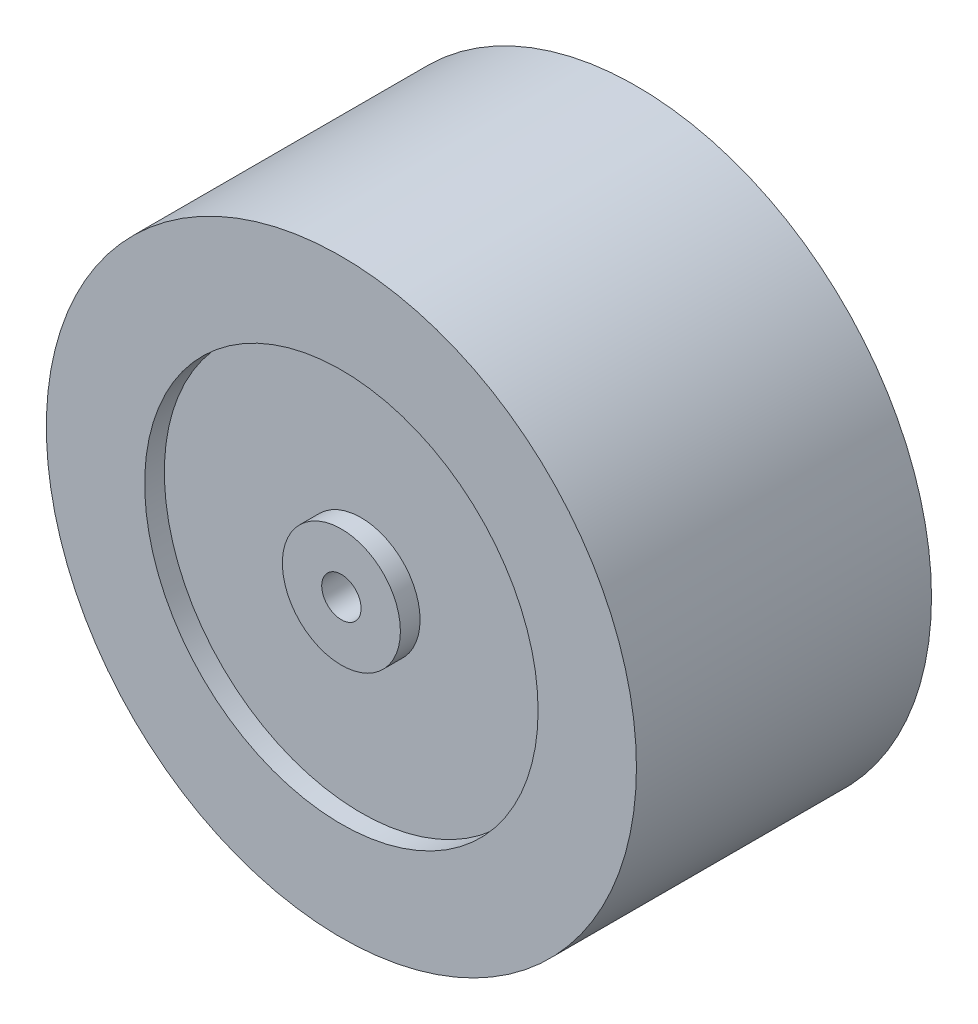
SolidWorks part; units mm, degrees
material "Nichtrostender Schmiedestahl"
ref_plane "Ebene vorne" through (0, 0, 0) normal (0, 0, 1) x (1, 0, 0)
ref_plane "Ebene oben" through (0, 0, 0) normal (0, 1, 0) x (1, 0, 0)
ref_plane "Ebene rechts" through (0, 0, 0) normal (1, 0, 0) x (0, 0, -1)
sketch "Skizze1" plane through (0, 0, 0) normal (0, 0, 1) x (1, 0, 0)
  circle A0 centre (0, 0) radius 300
  dimension "D1" = 600
extrude "Aufsatz-Linear austragen1" add sketch "Skizze1" along normal blind 300
sketch "Skizze2" plane through (0, 0, 300) normal (0, 0, 1) x (1, 0, 0)
  circle A0 centre (0, 0) radius 20
  dimension "D1" = 40
extrude "Schnitt-Linear austragen1" cut sketch "Skizze2" against normal blind 300
sketch "Skizze3" plane through (0, 0, 300) normal (0, 0, 1) x (1, 0, 0)
  circle A0 centre (0, 0) radius 60
  circle A1 centre (0, 0) radius 200
  dimension "D1" = 400
extrude "Schnitt-Linear austragen2" cut sketch "Skizze3" against normal blind 20
